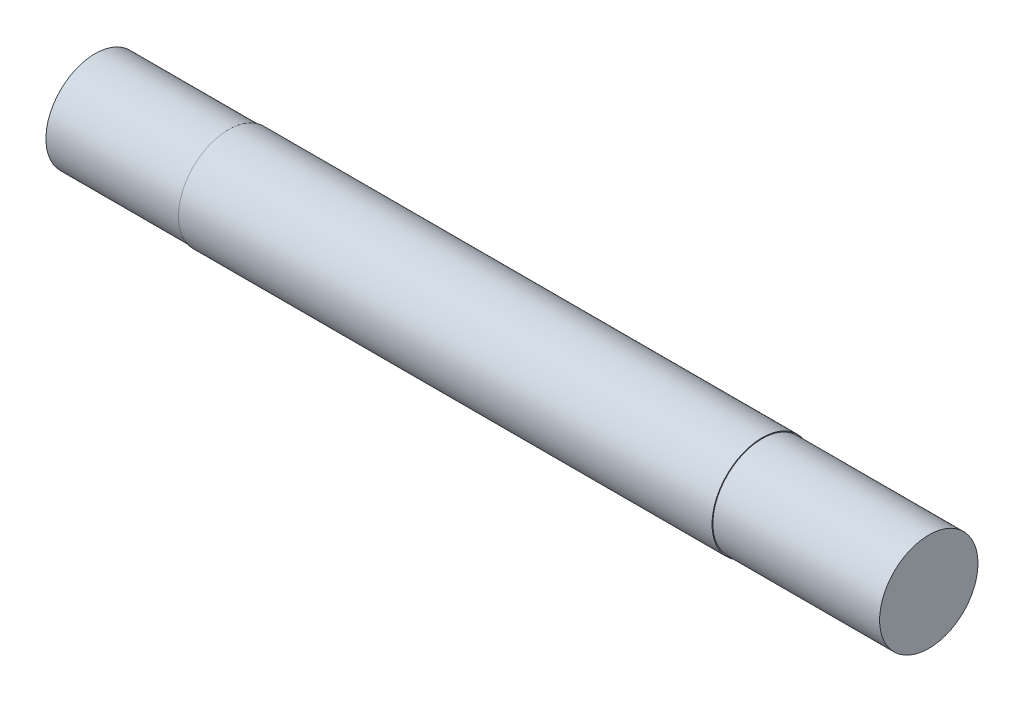
SolidWorks part; units mm, degrees
material "AISI 1020"
ref_plane "Front Plane" through (0, 0, 0) normal (0, 0, 1) x (1, 0, 0)
ref_plane "Top Plane" through (0, 0, 0) normal (0, 1, 0) x (1, 0, 0)
ref_plane "Right Plane" through (0, 0, 0) normal (1, 0, 0) x (0, 0, -1)
sketch "Sketch1" plane through (0, 0, 0) normal (0, 1, 0) x (1, 0, 0)
  line L0 (0, 0) -> (-9.079, 0) construction
  line L1 (0, 0) -> (8, 0)
  line L2 (0, 0) -> (0, 2.95)
  line L3 (0, 2.95) -> (8, 2.95)
  line L5 (8, 0) -> (40, 0)
  line L6 (8, 2.95) -> (8, 3)
  line L7 (8, 3) -> (40, 3)
  line L8 (40, 2.95) -> (40, 3)
  line L9 (40, 0) -> (50, 0)
  line L11 (40, 2.95) -> (50, 2.95)
  line L12 (50, 0) -> (50, 2.95)
  dimension "D1" = 5.9
  dimension "D2" = 8
  dimension "D3" = 6
  dimension "D4" = 50
  dimension "D5" = 10
  dimension "D6" = 50
revolve "Revolve1" add sketch "Sketch1" angle 360 about L0
cosmetic thread "Representação de rosca1" parameters "D2"=4.891
